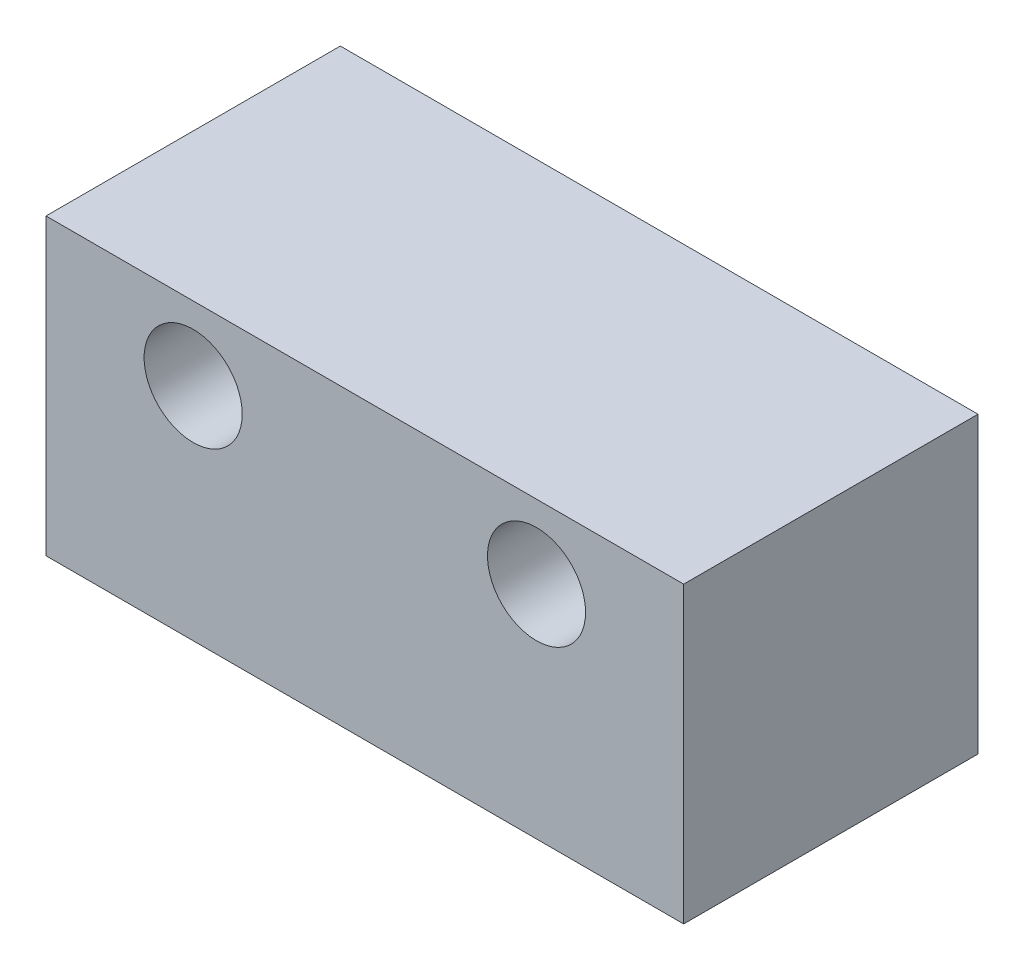
SolidWorks part; units mm, degrees
ref_plane "前视基准面" through (0, 0, 0) normal (0, 0, 1) x (1, 0, 0)
ref_plane "上视基准面" through (0, 0, 0) normal (0, 1, 0) x (1, 0, 0)
ref_plane "右视基准面" through (0, 0, 0) normal (1, 0, 0) x (0, 0, -1)
sketch "草图1" plane through (0, 0, 0) normal (0, 0, 1) x (1, 0, 0)
  line L1 (0, 0) -> (13, 0)
  line L2 (0, 0) -> (0, 6)
  line L3 (0, 6) -> (13, 6)
  line L4 (13, 0) -> (13, 6)
  dimension "D1" = 13
  dimension "D2" = 6
extrude "凸台-拉伸1" add sketch "草图1" along normal blind 6 contours L3 L4 L1 L2
sketch "草图2" plane through (0, 0, 6) normal (0, 0, 1) x (1, 0, 0)
  line L0 (0, 6) -> (13, 6) construction
  line L1 (0, 0) -> (0, 6) construction
  line L2 (13, 0) -> (13, 6) construction
  circle A0 centre (3, 4.5) radius 1
  circle A1 centre (10, 4.5) radius 1
  dimension "D1" = 2
  dimension "D2" = 2
  dimension "D3" = 1.5
  dimension "D4" = 1.5
  dimension "D5" = 3
  dimension "D6" = 3
extrude "切除-拉伸1" cut sketch "草图2" against normal blind 6
